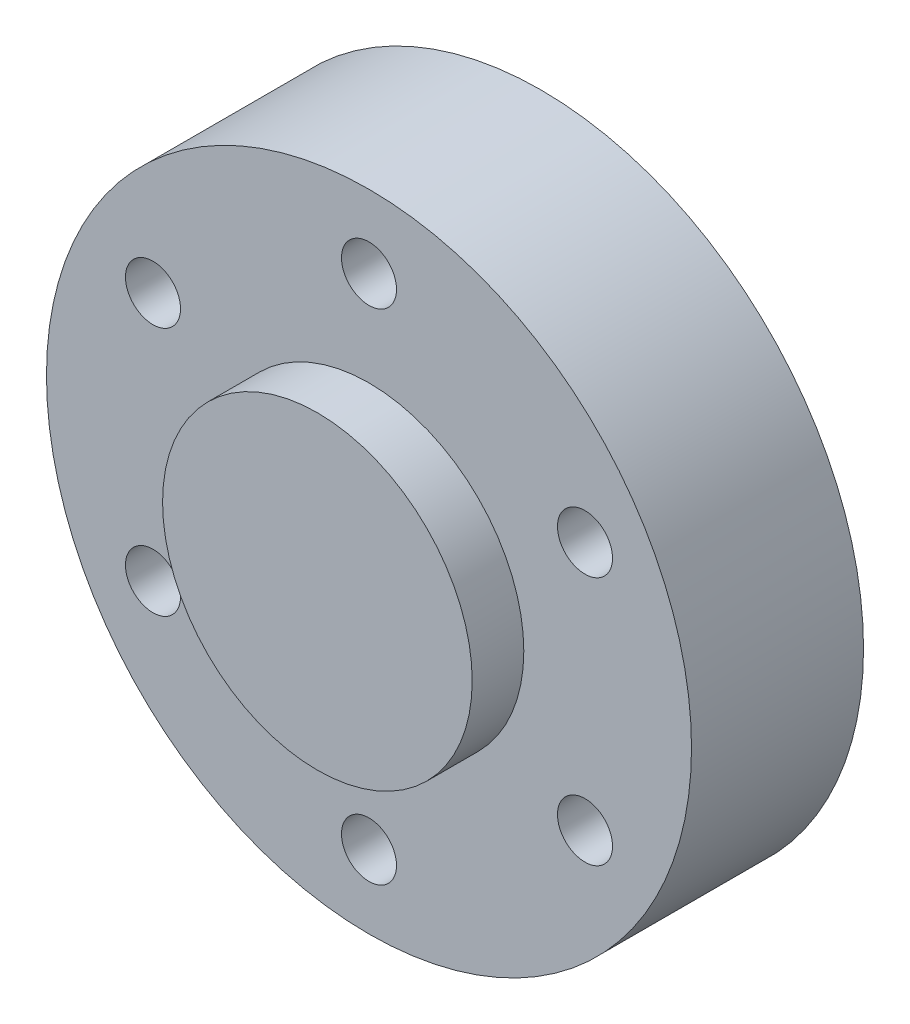
SolidWorks part; units mm, degrees
ref_plane "Front Plane" through (0, 0, 0) normal (0, 0, 1) x (1, 0, 0)
ref_plane "Top Plane" through (0, 0, 0) normal (0, 1, 0) x (1, 0, 0)
ref_plane "Right Plane" through (0, 0, 0) normal (1, 0, 0) x (0, 0, -1)
sketch "Sketch2" plane through (0, 0, 0) normal (0, 0, 1) x (1, 0, 0)
  circle A0 centre (0, 0) radius 9.5
  circle A1 centre (0, 0) radius 14.5 construction
  circle A3 centre (0, 0) radius 18.75
  circle A4 centre (0, 14.5) radius 1.6
  circle A5 centre (12.5574, 7.25) radius 1.6
  circle A6 centre (12.5574, -7.25) radius 1.6
  circle A7 centre (0, -14.5) radius 1.6
  circle A8 centre (-12.5574, -7.25) radius 1.6
  circle A9 centre (-12.5574, 7.25) radius 1.6
  point P21 (0, 0)
  dimension "D1" = 19
  dimension "D3" = 29
  dimension "D4" = 37.5
  dimension "D5" = 3.2
  dimension "D6" = 6
extrude "Boss-Extrude1" add sketch "Sketch2" along normal blind 10
sketch "Sketch3" plane through (0, 0, 10) normal (0, 0, 1) x (1, 0, 0)
  circle A0 centre (0, 0) radius 9
  dimension "D1" = 18
extrude "Boss-Extrude2" add sketch "Sketch3" along normal blind 3
sketch "Sketch6" plane through (0, 0, 0) normal (0, 0, -1) x (-1, 0, 0)
  circle A0 centre (0, 0) radius 9
  dimension "D1" = 18
extrude "Boss-Extrude4" add sketch "Sketch6" along normal blind 3 contours A0
sketch "Sketch7" plane through (0, 0, -3) normal (0, 0, -1) x (-1, 0, 0)
  circle A0 centre (0, 0) radius 1.6
  dimension "D1" = 3.2
extrude "Boss-Extrude5" add sketch "Sketch7" along normal blind 1
fillet "Fillet2" radius 0.05 1 edges at (-1.6, 0, -4)
sketch "Sketch9" plane through (0, 0, -4) normal (0, 0, -1) x (-1, 0, 0)
  circle A0 centre (0, 0) radius 1.4
  dimension "D1" = 2.8
extrude "Cut-Extrude1" cut sketch "Sketch9" against normal blind 10
